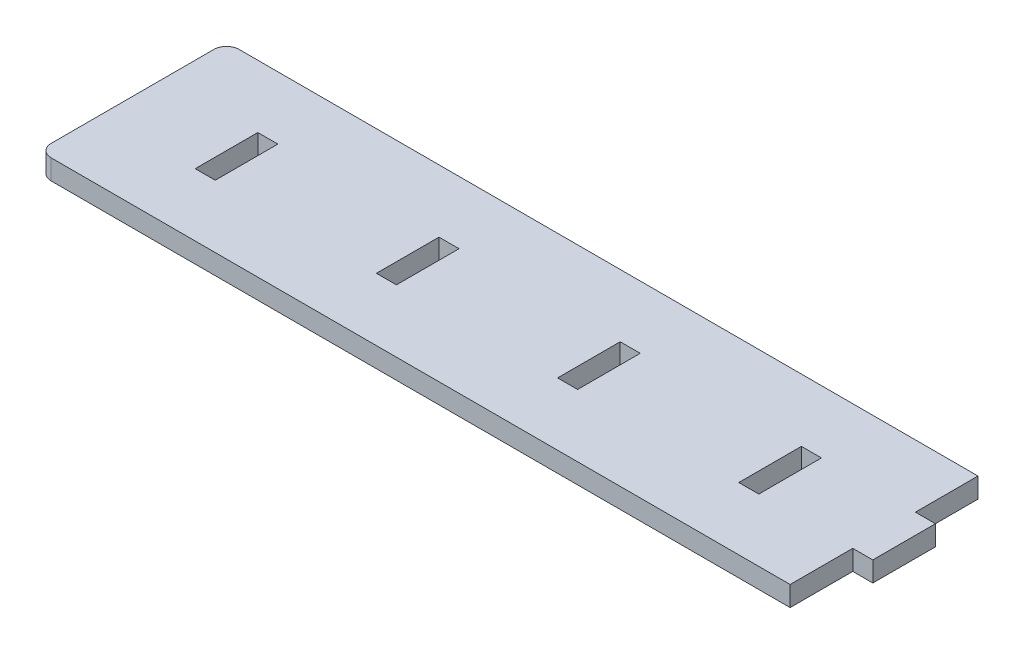
SolidWorks part; units mm, degrees
material "Oak"
ref_plane "Front Plane" through (0, 0, 0) normal (0, 0, 1) x (1, 0, 0)
ref_plane "Top Plane" through (0, 0, 0) normal (0, 1, 0) x (1, 0, 0)
ref_plane "Right Plane" through (0, 0, 0) normal (1, 0, 0) x (0, 0, -1)
sketch "Base_Sketch" plane through (0, 0, 0) normal (0, 1, 0) x (1, 0, 0)
  line L0 (0, -13917.5258) -> (0, 39432.9897) construction
  line L1 (-27603.0928, 0) -> (35335.0515, 0) construction
  line L2 (-16.0667, 5) -> (-12.8667, 5)
  line L3 (-60, 15) -> (60, 15)
  line L4 (-60, 15) -> (-60, -15)
  line L5 (-60, -15) -> (60, -15)
  line L6 (60, 15) -> (60, -15) construction
  line L7 (-60, 15) -> (60, -15) construction
  line L8 (-60, -15) -> (60, 15) construction
  line L9 (-45, 5) -> (-41.8, 5)
  line L10 (-45, 5) -> (-45, -5)
  line L11 (-45, -5) -> (-41.8, -5)
  line L12 (-41.8, 5) -> (-41.8, -5)
  line L13 (-45, 5) -> (-41.8, -5) construction
  line L14 (-45, -5) -> (-41.8, 5) construction
  line L15 (-16.0667, 5) -> (-12.8667, -5) construction
  line L16 (-16.0667, -5) -> (-12.8667, 5) construction
  line L17 (-12.8667, 5) -> (-12.8667, -5)
  line L18 (-16.0667, 5) -> (-16.0667, -5)
  line L19 (-16.0667, -5) -> (-12.8667, -5)
  line L20 (12.8667, 5) -> (16.0667, 5)
  line L21 (12.8667, 5) -> (16.0667, -5) construction
  line L22 (12.8667, -5) -> (16.0667, 5) construction
  line L23 (16.0667, 5) -> (16.0667, -5)
  line L24 (12.8667, 5) -> (12.8667, -5)
  line L25 (12.8667, -5) -> (16.0667, -5)
  line L26 (41.8, 5) -> (45, 5)
  line L27 (41.8, 5) -> (45, -5) construction
  line L28 (41.8, -5) -> (45, 5) construction
  line L29 (45, 5) -> (45, -5)
  line L30 (41.8, 5) -> (41.8, -5)
  line L31 (41.8, -5) -> (45, -5)
  line L32 (-41.8, 5) -> (-16.0667, 5) construction
  line L33 (-12.8667, 5) -> (12.8667, 5) construction
  line L34 (16.0667, 5) -> (41.8, 5) construction
  line L35 (-45, 0) -> (-60, 0) construction
  line L36 (45, 0) -> (60, 0) construction
  line L37 (60, -15) -> (60, -5)
  line L38 (60, -5) -> (63.2, -5)
  line L39 (63.2, -5) -> (63.2, 5)
  line L40 (63.2, 5) -> (60, 5)
  line L41 (60, 5) -> (60, 15)
  point P1 (0, 0)
  point P10 (-43.4, 0)
  point P15 (14.4667, 0)
  point P16 (-14.4667, 0)
  point P25 (43.4, 0)
  dimension "D1" = 30
  dimension "D2" = 120
  dimension "D3" = 10
  dimension "D4" = 3.2
  dimension "D6" = 90
  dimension "D7" = 3.2
  dimension "D5" = 4
extrude "Boss-Extrude1" add sketch "Base_Sketch" along normal blind 3.2
fillet "Fillet1" radius 2 2 edges at (-60, 1.6, -15) (-60, 1.6, 15)
equation "\"Material_Thickness\"= \"Material_Thickness@Soldering_Jig.Assembly\""
equation "\"D4@Base_Sketch\" = \"Material_Thickness\""
equation "\"D1@Boss-Extrude1\"=\"Material_Thickness\""
equation "\"LED_Cube_Height\"= \"LED_Cube_Height@Soldering_Jig.Assembly\""
equation "\"D6@Base_Sketch\"=\"LED_Cube_Height\""
equation "\"D7@Base_Sketch\"=\"Material_Thickness\""
